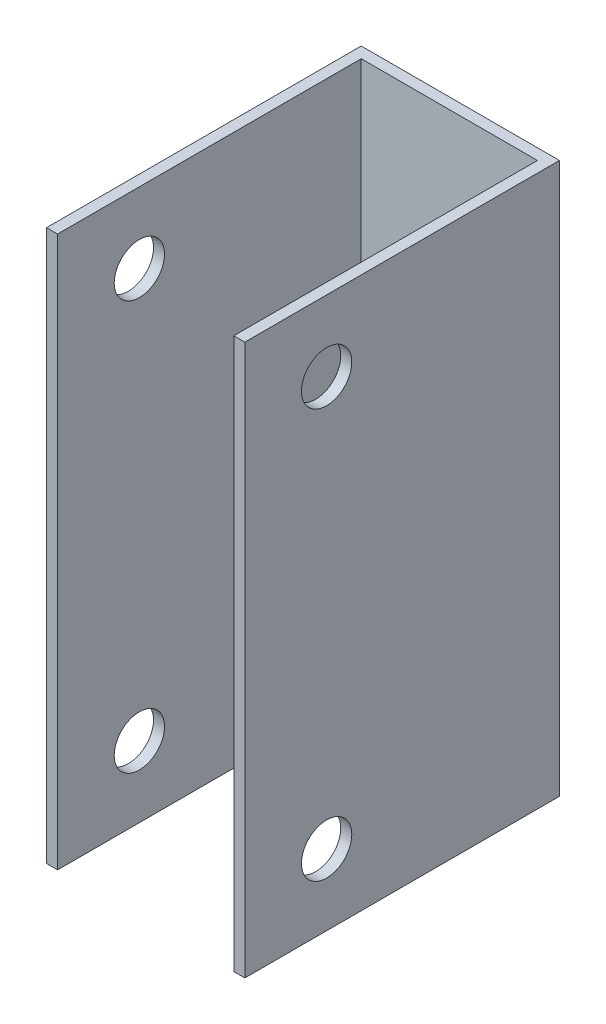
SolidWorks part; units mm, degrees
ref_plane "前视基准面" through (0, 0, 0) normal (0, 0, 1) x (1, 0, 0)
ref_plane "上视基准面" through (0, 0, 0) normal (0, 1, 0) x (1, 0, 0)
ref_plane "右视基准面" through (0, 0, 0) normal (1, 0, 0) x (0, 0, -1)
sketch "草图1" plane through (0, 0, 0) normal (0, 1, 0) x (1, 0, 0)
  line L0 (0, 0) -> (0, 20)
  line L1 (0, 20) -> (12.6, 20)
  line L2 (12.6, 20) -> (12.6, 9.502)
  line L3 (0.7, 0) -> (0.7, 19.3)
  line L4 (0.7, 19.3) -> (11.9, 19.3)
  line L5 (11.9, 19.3) -> (11.9, 0)
  line L11 (12.6, 9.502) -> (12.6, 0)
  line L12 (12.6, 20) -> (12.6, 0) construction
  line L13 (11.9, 0) -> (12.6, 0)
  line L14 (0.7, 0) -> (0, 0)
  point P10 (12.6, 9.4084)
  point P11 (12.6, 19.8505)
  dimension "D3" = 11.2
  dimension "D5" = 20
  dimension "D1" = 0.7
extrude "凸台-拉伸1" add sketch "草图1" along normal blind 35
sketch "草图2" plane through (0, 0, 0) normal (-1, 0, 0) x (0, 0, 1)
  line L1 (0, 35) -> (0, 0) construction
  line L2 (0, 17.5) -> (-15.9992, 17.5) construction
  circle A0 centre (-5.2, 30.5) radius 1.6
  circle A1 centre (-5.2, 4.5) radius 1.6
  dimension "D2" = 5.2
  dimension "D3" = 3.2
  dimension "D4" = 26
extrude "切除-拉伸1" cut sketch "草图2" against normal through all
